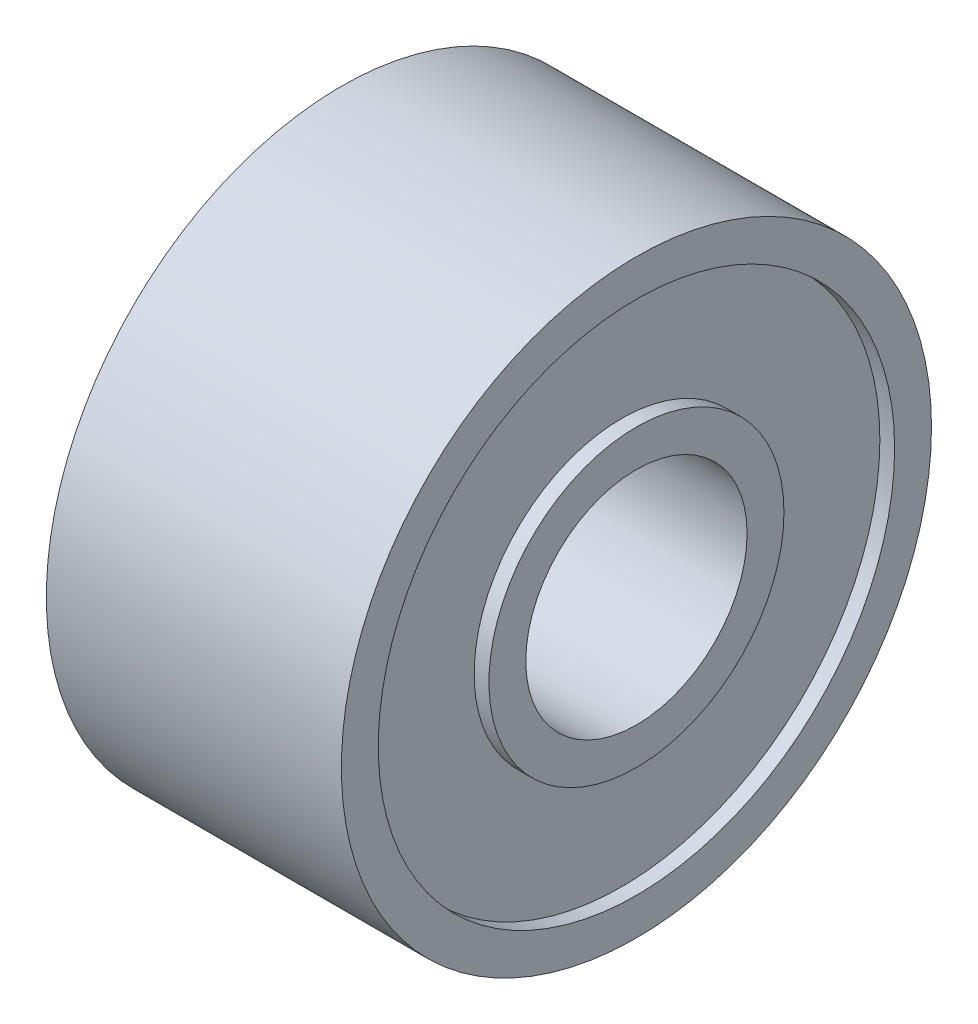
SolidWorks part; units mm, degrees
ref_plane "Front Plane" through (0, 0, 0) normal (0, 0, 1) x (1, 0, 0)
ref_plane "Top Plane" through (0, 0, 0) normal (0, 1, 0) x (1, 0, 0)
ref_plane "Right Plane" through (0, 0, 0) normal (1, 0, 0) x (0, 0, -1)
sketch "Sketch1" plane through (0, 0, 0) normal (1, 0, 0) x (0, 0, -1)
  circle A0 centre (0, 0) radius 1.5
  circle A1 centre (0, 0) radius 4
  dimension "D1" = 8
  dimension "D2" = 3
extrude "Boss-Extrude1" add sketch "Sketch1" along normal blind 4
sketch "Sketch2" plane through (4, 0, 0) normal (1, 0, 0) x (0, 0, -1)
  circle A0 centre (0, 0) radius 3.5
  circle A1 centre (0, 0) radius 2
  circle A2 centre (0, 0) radius 1.5 construction
  circle A3 centre (0, 0) radius 4 construction
  dimension "D1" = 0.5
  dimension "D2" = 0.5
extrude "Cut-Extrude1" cut sketch "Sketch2" against normal blind 0.2
sketch "Sketch3" plane through (0, 0, 0) normal (-1, 0, 0) x (0, 0, 1)
  circle A1 centre (0, 0) radius 2
  circle A2 centre (0, 0) radius 2
  circle A3 centre (0, 0) radius 3.5
  circle A4 centre (0, 0) radius 3.5
  dimension "D1" = 0
  dimension "D2" = 0
extrude "Cut-Extrude2" cut sketch "Sketch3" against normal blind 0.2
